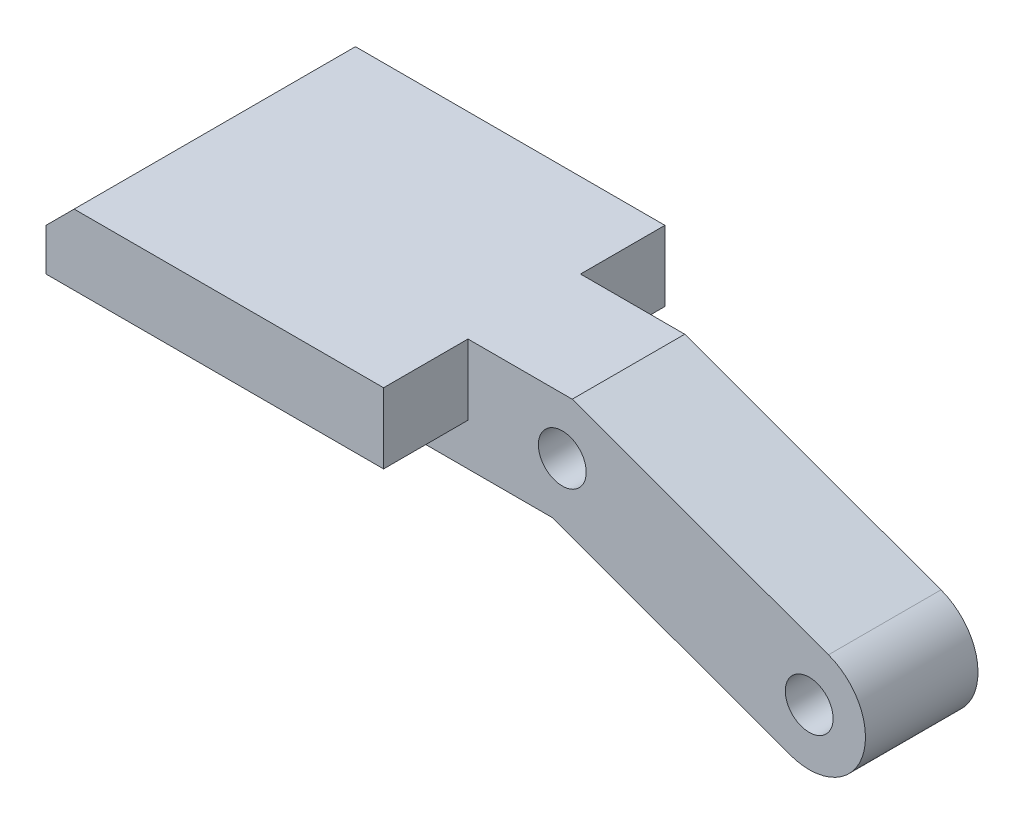
SolidWorks part; units mm, degrees
ref_plane "前视基准面" through (0, 0, 0) normal (0, 0, 1) x (1, 0, 0)
ref_plane "上视基准面" through (0, 0, 0) normal (0, 1, 0) x (1, 0, 0)
ref_plane "右视基准面" through (0, 0, 0) normal (1, 0, 0) x (0, 0, -1)
sketch "草图1" plane through (0, 0, 0) normal (0, 0, 1) x (1, 0, 0)
  line L0 (-1.3681, -3.7588) -> (-18.2588, 2.3889)
  line L1 (-18.2588, 2.3889) -> (-48.2588, 2.3889)
  line L2 (-48.2588, 2.3889) -> (-48.2588, 10.3889)
  line L3 (-48.2588, 10.3889) -> (-16.8482, 10.3889)
  line L4 (-16.8482, 10.3889) -> (1.3681, 3.7588)
  line L5 (-18.2588, 2.3889) -> (-16.8482, 10.3889) construction
  arc A0 (-1.3681, -3.7588) -> (1.3681, 3.7588) centre (0, 0) ccw
  circle A1 centre (-17.5535, 6.3889) radius 1.5292 construction
  dimension "D1" = 8
  dimension "D2" = 18.68
  dimension "D3" = 30
  dimension "D4" = 8
  dimension "D5" = 160
extrude "凸台-拉伸1" add sketch "草图1" along normal blind 8
sketch "草图2" plane through (0, 0, 8) normal (0, 0, 1) x (1, 0, 0)
  circle A0 centre (0, 0) radius 1.7
  dimension "D1" = 3.4
extrude "切除-拉伸1" cut sketch "草图2" against normal blind 8
sketch "草图3" plane through (0, 0, 8) normal (0, 0, 1) x (1, 0, 0)
  line L0 (-16.8482, 10.3889) -> (-18.2588, 2.3889) construction
  circle A0 centre (-17.5535, 6.3889) radius 1.7
  dimension "D1" = 3.4
extrude "切除-拉伸2" cut sketch "草图3" against normal blind 8
sketch "草图4" plane through (0, 10.3889, 0) normal (0, 1, 0) x (1, 0, 0)
  line L0 (-16.8482, 0) -> (-48.2588, -8) construction
  line L1 (-24.2588, 6) -> (-48.2588, 6)
  line L2 (-24.2588, 6) -> (-24.2588, -14)
  line L3 (-24.2588, -14) -> (-48.2588, -14)
  line L4 (-48.2588, 6) -> (-48.2588, -14)
  line L5 (-24.2588, 6) -> (-48.2588, -14) construction
  line L6 (-24.2588, -14) -> (-48.2588, 6) construction
  line L7 (-48.2588, -8) -> (-48.2588, 0) construction
  line L8 (-36.2588, -4) -> (-48.2588, -4) construction
  point P0 (-36.2588, -4)
  dimension "D1" = 20
  dimension "D2" = 12
extrude "凸台-拉伸2" add sketch "草图4" against normal blind 5
chamfer "倒角1" distance 2 angle 45 1 edges at (-48.2588, 10.3889, 4)
